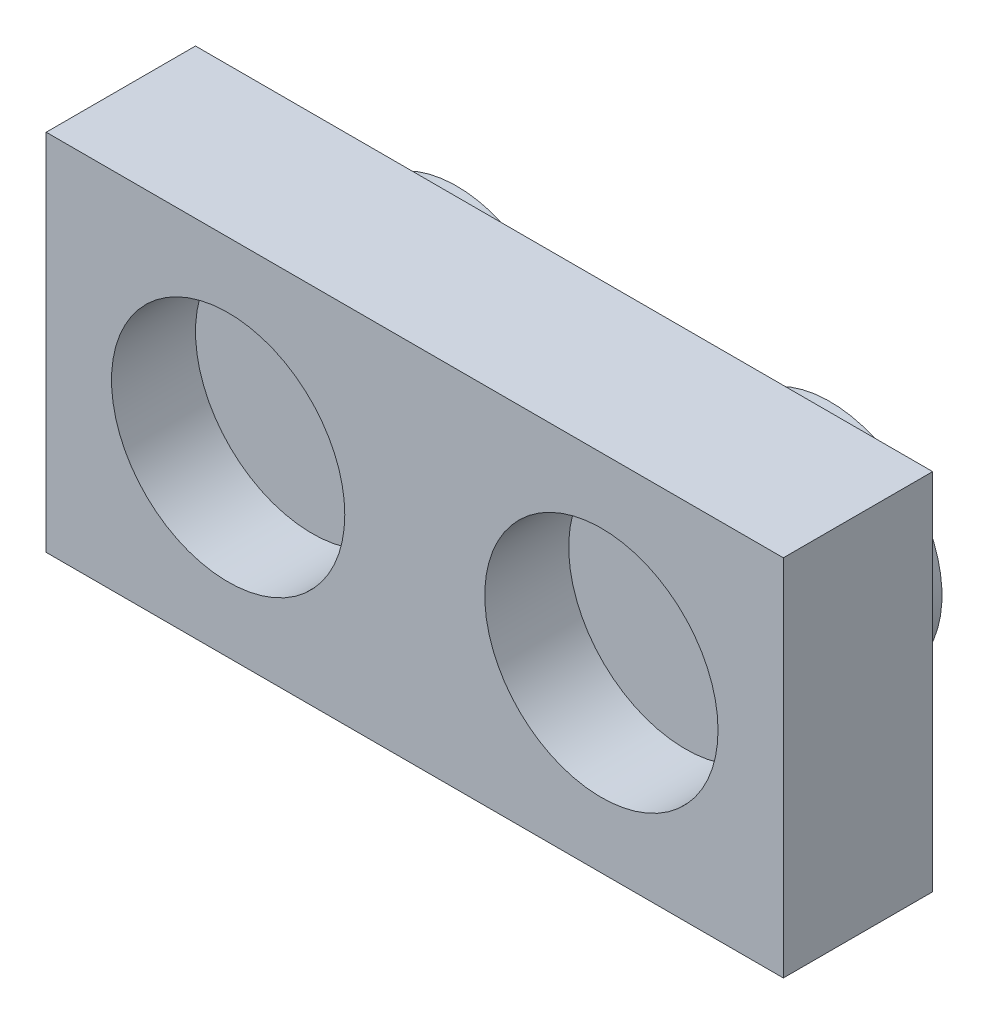
SolidWorks part; units mm, degrees
ref_plane "Спереди" through (0, 0, 0) normal (0, 0, 1) x (1, 0, 0)
ref_plane "Сверху" through (0, 0, 0) normal (0, 1, 0) x (1, 0, 0)
ref_plane "Справа" through (0, 0, 0) normal (1, 0, 0) x (0, 0, -1)
sketch "Эскиз1" plane through (0, 0, 0) normal (0, 0, 1) x (1, 0, 0)
  line L1 (-7.9, -3.9) -> (7.9, -3.9)
  line L2 (-7.9, -3.9) -> (-7.9, 3.9)
  line L3 (-7.9, 3.9) -> (7.9, 3.9)
  line L4 (7.9, -3.9) -> (7.9, 3.9)
  line L5 (-7.9, -3.9) -> (7.9, 3.9) construction
  line L6 (-7.9, 3.9) -> (7.9, -3.9) construction
  point P0 (0, 0)
  dimension "D1" = 15.8
  dimension "D2" = 7.8
extrude "Бобышка-Вытянуть1" add sketch "Эскиз1" along normal blind 3.2
sketch "Эскиз2" plane through (0, 0, 0) normal (0, 0, -1) x (-1, 0, 0)
  circle A0 centre (-4, 0) radius 2.4
  circle A1 centre (4, 0) radius 2.4
  point P4 (0, 0)
  dimension "D1" = 4
  dimension "D2" = 4
extrude "Бобышка-Вытянуть2" add sketch "Эскиз2" along normal blind 1.7
sketch "Эскиз3" plane through (0, 0, 3.2) normal (0, 0, 1) x (1, 0, 0)
  circle A0 centre (-4, 0) radius 2.5
  circle A1 centre (4, 0) radius 2.5
  dimension "D1" = 4
  dimension "D2" = 4
extrude "Вырез-Вытянуть1" cut sketch "Эскиз3" against normal blind 1.8
